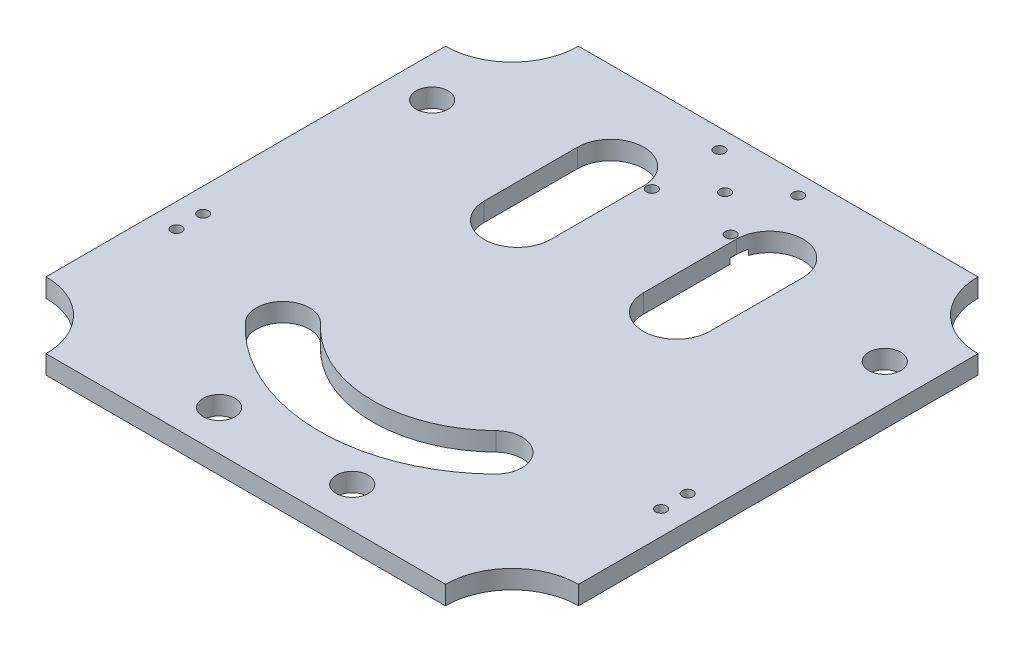
SolidWorks part; units mm, degrees
ref_plane "Front Plane" through (0, 0, 0) normal (0, 0, 1) x (1, 0, 0)
ref_plane "Top Plane" through (0, 0, 0) normal (0, 1, 0) x (1, 0, 0)
ref_plane "Right Plane" through (0, 0, 0) normal (1, 0, 0) x (0, 0, -1)
sketch "Sketch1" plane through (0, 0, 0) normal (0, 1, 0) x (1, 0, 0)
  line L0 (-29.8709, 66.9249) -> (-29.8709, 31.9249) construction
  line L1 (-75, 100) -> (75, 100)
  line L2 (-100, 75) -> (-100, -75)
  line L3 (-75, -100) -> (75, -100)
  line L4 (100, 75) -> (100, -75)
  line L5 (-82.3223, 82.3223) -> (82.3223, -82.3223) construction
  line L6 (-82.3223, -82.3223) -> (82.3223, 82.3223) construction
  line L7 (-17.3709, 66.9249) -> (-17.3709, 31.9249)
  line L8 (-42.3709, 66.9249) -> (-42.3709, 31.9249)
  line L9 (0, 0) -> (0, 161.9718) construction
  line L10 (29.8709, 66.9249) -> (29.8709, 31.9249) construction
  line L11 (17.3709, 66.9249) -> (17.3709, 31.9249)
  line L12 (42.3709, 66.9249) -> (42.3709, 31.9249)
  arc A0 (-75, -100) -> (-100, -75) centre (-100, -100) ccw
  arc A1 (-75, 100) -> (-100, 75) centre (-100, 100) cw
  arc A2 (100, 75) -> (75, 100) centre (100, 100) cw
  arc A3 (100, -75) -> (75, -100) centre (100, -100) ccw
  circle A4 centre (-85, 55) radius 6
  circle A5 centre (85, 55) radius 6
  circle A6 centre (25, -85) radius 6
  circle A7 centre (-25, -85) radius 6
  arc A8 (-17.3709, 66.9249) -> (-42.3709, 66.9249) centre (-29.8709, 66.9249) ccw
  arc A9 (-42.3709, 31.9249) -> (-17.3709, 31.9249) centre (-29.8709, 31.9249) ccw
  arc A10 (17.3709, 66.9249) -> (42.3709, 66.9249) centre (29.8709, 66.9249) cw
  arc A11 (42.3709, 31.9249) -> (17.3709, 31.9249) centre (29.8709, 31.9249) cw
  arc A12 (41.4714, -47.7195) -> (-40.4344, -45.5682) centre (1.5695, -6.6301) cw construction
  arc A13 (-47.768, -52.3666) -> (48.438, -54.8935) centre (1.5695, -6.6301) ccw
  arc A14 (-33.1007, -38.7698) -> (34.5048, -40.5455) centre (1.5695, -6.6301) ccw
  arc A15 (-33.1007, -38.7698) -> (-47.768, -52.3666) centre (-40.4344, -45.5682) ccw
  arc A16 (48.438, -54.8935) -> (34.5048, -40.5455) centre (41.4714, -47.7195) ccw
  point P0 (0, 0)
  point P18 (-25, -85)
  point P19 (-25, -85)
  point P20 (25, -85)
  point P21 (85, 55)
  point P22 (-85, 55)
  point P23 (85, 55)
  point P24 (-85, 55)
  point P35 (-29.8709, 49.4249)
  point P44 (29.8709, 49.4249)
  point P52 (0.0656, -63.886)
  dimension "D1" = 200
  dimension "D2" = 200
extrude "Boss-Extrude2" add sketch "Sketch1" along normal blind 7
sketch "Sketch2" plane through (0, 7, 0) normal (0, 1, 0) x (1, 0, 0)
  circle A0 centre (-91, -25) radius 2
  circle A1 centre (0, 80) radius 2
  circle A2 centre (91, -25) radius 2
  point P0 (-91, -25)
  point P1 (0, 80)
  point P2 (91, -25)
extrude "Cut-Extrude1" cut sketch "Sketch2" against normal through all
sketch "Sketch3" plane through (0, 7, 0) normal (0, 1, 0) x (1, 0, 0)
  circle A0 centre (-91, -35) radius 2
  circle A1 centre (91, -35) radius 2
  point P0 (-91, -35)
  point P1 (-91, -25)
  point P2 (-91, -35)
  point P6 (91, -25)
  point P7 (91, -35)
extrude "Cut-Extrude3" cut sketch "Sketch3" against normal through all
sketch "Sketch4" plane through (0, 7, 0) normal (0, 1, 0) x (1, 0, 0)
  line L1 (-17.5, 95) -> (17.5, 95) construction
  line L2 (-17.5, 95) -> (-17.5, 65) construction
  line L3 (-17.5, 65) -> (17.5, 65) construction
  line L4 (17.5, 95) -> (17.5, 65) construction
  line L5 (-17.5, 95) -> (17.5, 65) construction
  line L6 (-17.5, 65) -> (17.5, 95) construction
  circle A0 centre (-14.796, 67.317) radius 2
  circle A1 centre (-14.796, 92.683) radius 2
  circle A2 centre (14.7968, 92.683) radius 2
  circle A3 centre (14.7968, 67.317) radius 2
  point P0 (-14.796, 67.317)
  point P1 (-14.796, 65)
  point P4 (-14.796, 67.317)
  point P7 (0, 80)
  point P8 (-14.796, 67.317)
  point P11 (-14.796, 92.683)
  point P12 (14.7968, 92.683)
  point P13 (14.7968, 67.317)
  dimension "D1" = 30
  dimension "D2" = 35
extrude "Cut-Extrude4" cut sketch "Sketch4" against normal through all
sketch "Sketch5" plane through (0, 0, 0) normal (0, -1, 0) x (1, 0, 0)
  line L1 (-18, -64.5) -> (18, -64.5)
  line L2 (-18, -64.5) -> (-18, -95.5)
  line L3 (-18, -95.5) -> (18, -95.5)
  line L4 (18, -64.5) -> (18, -95.5)
  line L5 (-18, -64.5) -> (18, -95.5) construction
  line L6 (-18, -95.5) -> (18, -64.5) construction
  point P0 (0, -80)
  dimension "D1" = 36
  dimension "D2" = 31
extrude "Cut-Extrude7" cut sketch "Sketch5" against normal blind 2
